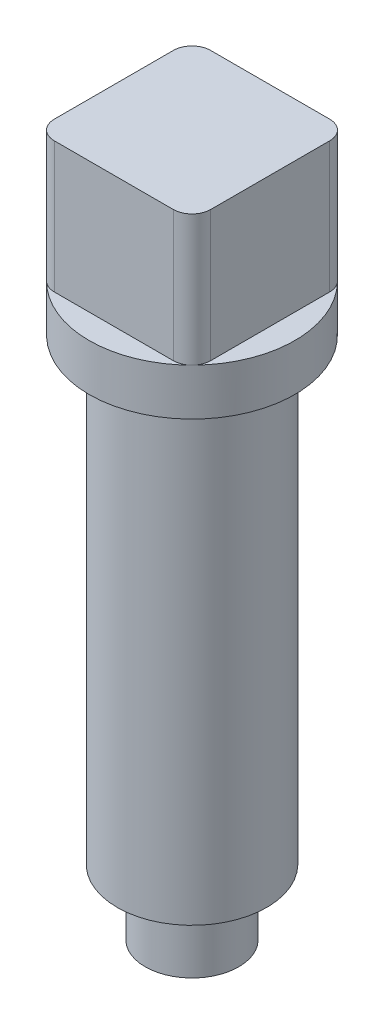
SolidWorks part; units mm, degrees
ref_plane "Front Plane" through (0, 0, 0) normal (0, 0, 1) x (1, 0, 0)
ref_plane "Top Plane" through (0, 0, 0) normal (0, 1, 0) x (1, 0, 0)
ref_plane "Right Plane" through (0, 0, 0) normal (1, 0, 0) x (0, 0, -1)
sketch "Sketch1" plane through (0, 0, 0) normal (0, 0, 1) x (1, 0, 0)
  line L0 (0, 0) -> (5, 0)
  line L1 (5, 0) -> (5, 7)
  line L2 (5, 7) -> (8, 7)
  line L3 (8, 7) -> (8, 56)
  line L4 (8, 56) -> (11, 56)
  line L5 (11, 56) -> (11, 61)
  line L6 (11, 61) -> (0, 61)
  line L7 (0, 61) -> (0, 0) construction
  line L8 (0, 0) -> (0, 61)
  dimension "D1" = 5
  dimension "D2" = 49
  dimension "D3" = 7
  dimension "D4" = 8
  dimension "D5" = 11
  dimension "D6" = 5
revolve "Revolve1" add sketch "Sketch1" angle 360 about L7
cosmetic thread "Cosmetic Thread1" parameters "D2"=13.797
sketch "Sketch2" plane through (0, 61, 0) normal (0, 1, 0) x (1, 0, 0)
  line L1 (-6.364, 8.364) -> (6.364, 8.364)
  line L2 (-8.364, 6.364) -> (-8.364, -6.364)
  line L3 (-6.364, -8.364) -> (6.364, -8.364)
  line L4 (8.364, 6.364) -> (8.364, -6.364)
  line L5 (-8.364, 8.364) -> (8.364, -8.364) construction
  line L6 (-8.364, -8.364) -> (8.364, 8.364) construction
  arc A3 (-6.364, 8.364) -> (-8.364, 6.364) centre (-6.364, 6.364) ccw
  arc A4 (-8.364, -6.364) -> (-6.364, -8.364) centre (-6.364, -6.364) ccw
  arc A5 (6.364, -8.364) -> (8.364, -6.364) centre (6.364, -6.364) ccw
  arc A6 (8.364, 6.364) -> (6.364, 8.364) centre (6.364, 6.364) ccw
  circle A7 centre (0, 0) radius 11 construction
  point P0 (0, 0)
  dimension "D1" = 2
extrude "Boss-Extrude2" add sketch "Sketch2" along normal blind 14
